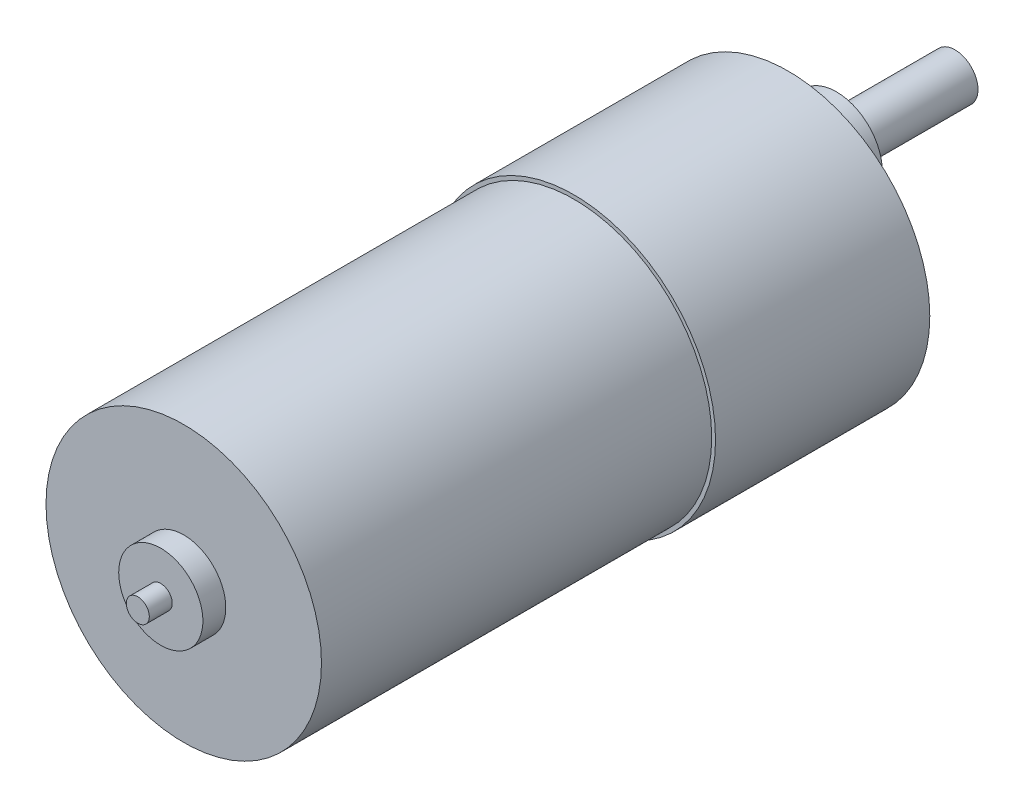
SolidWorks part; units mm, degrees
ref_plane "Front" through (0, 0, 0) normal (0, 0, 1) x (1, 0, 0)
ref_plane "Top" through (0, 0, 0) normal (0, 1, 0) x (1, 0, 0)
ref_plane "Right" through (0, 0, 0) normal (1, 0, 0) x (0, 0, -1)
sketch "Sketch1" plane through (0, 0, 0) normal (1, 0, 0) x (0, 0, -1)
  line L0 (33.871, 0) -> (-33.2903, 0) construction
  line L1 (0, 0) -> (0, -1.5)
  line L2 (0, -1.5) -> (3, -1.5)
  line L3 (3, -1.5) -> (3, -5.5)
  line L4 (3, -5.5) -> (6, -5.5)
  line L5 (6, -5.5) -> (6, -18)
  line L6 (6, -18) -> (57, -18)
  line L7 (57, -18) -> (57, -18.5)
  line L8 (57, -18.5) -> (85, -18.5)
  line L9 (85, -18.5) -> (85, 0)
  line L10 (85, 0) -> (0, 0)
  point P13 (57, -18.25)
  dimension "D1" = 1.5
  dimension "D2" = 5.5
  dimension "D3" = 18
  dimension "D4" = 18.5
  dimension "D5" = 57
  dimension "D6" = 54
  dimension "D7" = 51
  dimension "D8" = 28
revolve "Revolve1" add sketch "Sketch1" angle 360 about L0
sketch "Sketch2" plane through (0, 0, -85) normal (0, 0, -1) x (-1, 0, 0)
  line L0 (0, 0) -> (0, 7) construction
  circle A0 centre (0, 7) radius 6
  dimension "D2" = 12
  dimension "D1" = 7
extrude "Boss-Extrude1" add sketch "Sketch2" along normal blind 6.3
sketch "Sketch3" plane through (0, 0, -91.3) normal (0, 0, -1) x (-1, 0, 0)
  circle A0 centre (0, 7) radius 3
  circle A1 centre (0, 7) radius 6 construction
  dimension "D1" = 6
extrude "Boss-Extrude2" add sketch "Sketch3" along normal blind 15.5
hole_wizard "M3x0.5 Tapped Hole1" positions "Sketch4" profile "Sketch5" tap size "M3x0.5" standard "ANSI Metric"
sketch "Sketch4" plane through (0, 0, -85) normal (0, 0, -1) x (-1, 0, 0)
  line L0 (0, 0) -> (-15.5, 0) construction
  line L2 (15.5, 0) -> (0, 0) construction
  line L4 (0, 0) -> (7.75, 13.4234) construction
  line L6 (7.75, -13.4234) -> (0, 0) construction
  circle A0 centre (0, 0) radius 15.5 construction
  point P0 (7.75, -13.4234)
  point P2 (15.5, 0)
  point P4 (-15.5, 0)
  point P6 (7.75, 13.4234)
  dimension "D1" = 31
  dimension "D2" = 120
  dimension "D3" = 120
sketch "Sketch5" plane through (-7.75, -13.4234, -85) normal (1, 0, 0) x (0, 1, 0)
  line L0 (0, 0) -> (0, 4.2511)
  line L1 (0, 4.2511) -> (1.25, 3.5)
  line L2 (1.25, 3.5) -> (1.25, 0)
  line L5 (1.25, 0) -> (0, 0)
  line L10 (0, 4.2511) -> (-1.25, 3.5) construction
  line L11 (0, -6.35) -> (0, 107.95) construction
  dimension "Tap Drill Dia." = 2.5
  dimension "Tap Drill Depth" = 3.5
  dimension "Drill Angle" = 118
cosmetic thread "Hole Thread5" parameters "D1"=3.5, "D2"=3
cosmetic thread "Hole Thread6" parameters "D1"=3.5, "D2"=3
cosmetic thread "Hole Thread7" parameters "D1"=3.5, "D2"=3
cosmetic thread "Hole Thread8" parameters "D1"=3.5, "D2"=3
sketch "Sketch6" plane through (0, 0, -106.8) normal (0, 0, -1) x (-1, 0, 0)
  line L0 (-1.6583, 4.5) -> (1.6583, 4.5)
  line L1 (0, 4) -> (0, 4.5) construction
  circle A0 centre (0, 7) radius 3 construction
  arc A1 (-1.6583, 4.5) -> (1.6583, 4.5) centre (0, 7) ccw
  dimension "D1" = 0.5
extrude "Cut-Extrude1" cut sketch "Sketch6" against normal blind 12
